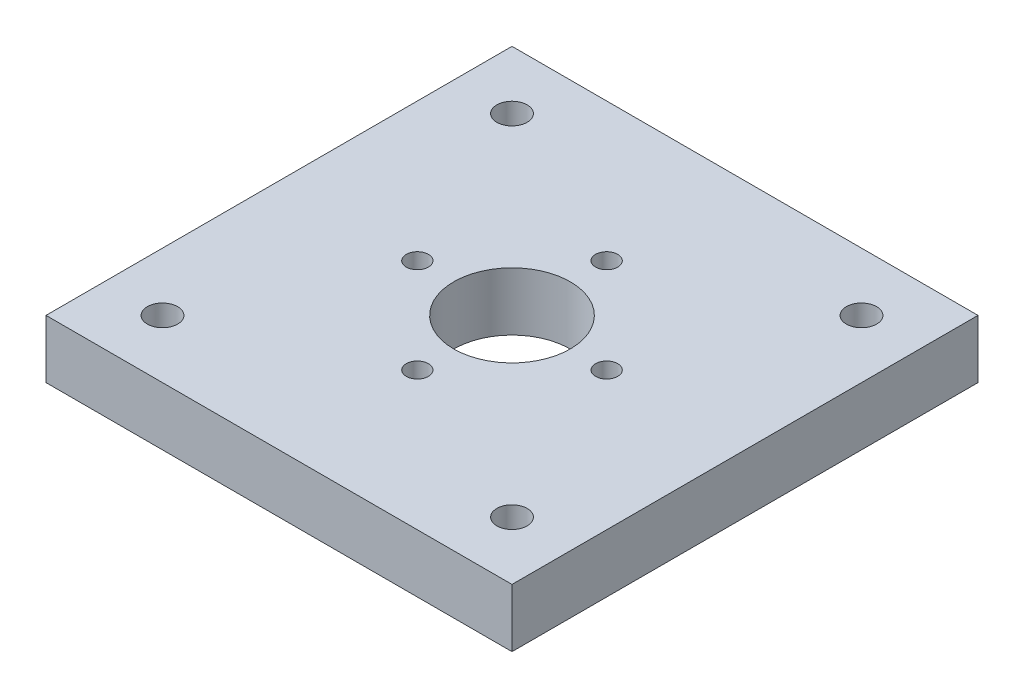
SolidWorks part; units mm, degrees
ref_plane "Front Plane" through (0, 0, 0) normal (0, 0, 1) x (1, 0, 0)
ref_plane "Top Plane" through (0, 0, 0) normal (0, 1, 0) x (1, 0, 0)
ref_plane "Right Plane" through (0, 0, 0) normal (1, 0, 0) x (0, 0, -1)
sketch "Sketch1" plane through (0, 0, 0) normal (0, 1, 0) x (1, 0, 0)
  line L0 (0, 3.0504) -> (0, -3.2142) construction
  line L1 (-2, 2) -> (2, 2)
  line L2 (-2, 2) -> (-2, -2)
  line L3 (-2, -2) -> (2, -2)
  line L4 (2, 2) -> (2, -2)
  line L5 (-2, 2) -> (2, -2) construction
  line L6 (-2, -2) -> (2, 2) construction
  line L7 (-3.6668, 0) -> (3.0564, 0) construction
  circle A0 centre (-1.5, 1.5) radius 0.13
  circle A1 centre (1.5, 1.5) radius 0.13
  circle A2 centre (1.5, -1.5) radius 0.13
  circle A3 centre (-1.5, -1.5) radius 0.13
  circle A4 centre (0, 0) radius 0.5
  circle A5 centre (0, 0) radius 0.8125 construction
  circle A6 centre (0, 0.8125) radius 0.095
  circle A7 centre (0.8125, 0) radius 0.095
  circle A8 centre (0, -0.8125) radius 0.095
  circle A9 centre (-0.8125, 0) radius 0.095
  point P0 (0, 0)
  point P32 (0, 0)
  dimension "D5" = 0.26
  dimension "D6" = 1
  dimension "D7" = 1.625
  dimension "D8" = 0.19
  dimension "D1" = 4
  dimension "D2" = 4
  dimension "D3" = 0.5
  dimension "D4" = 0.5
  dimension "D10" = 0.8125
  dimension "D11" = 0.8125
  dimension "D9" = 4
extrude "Boss-Extrude1" add sketch "Sketch1" along normal blind 0.5
